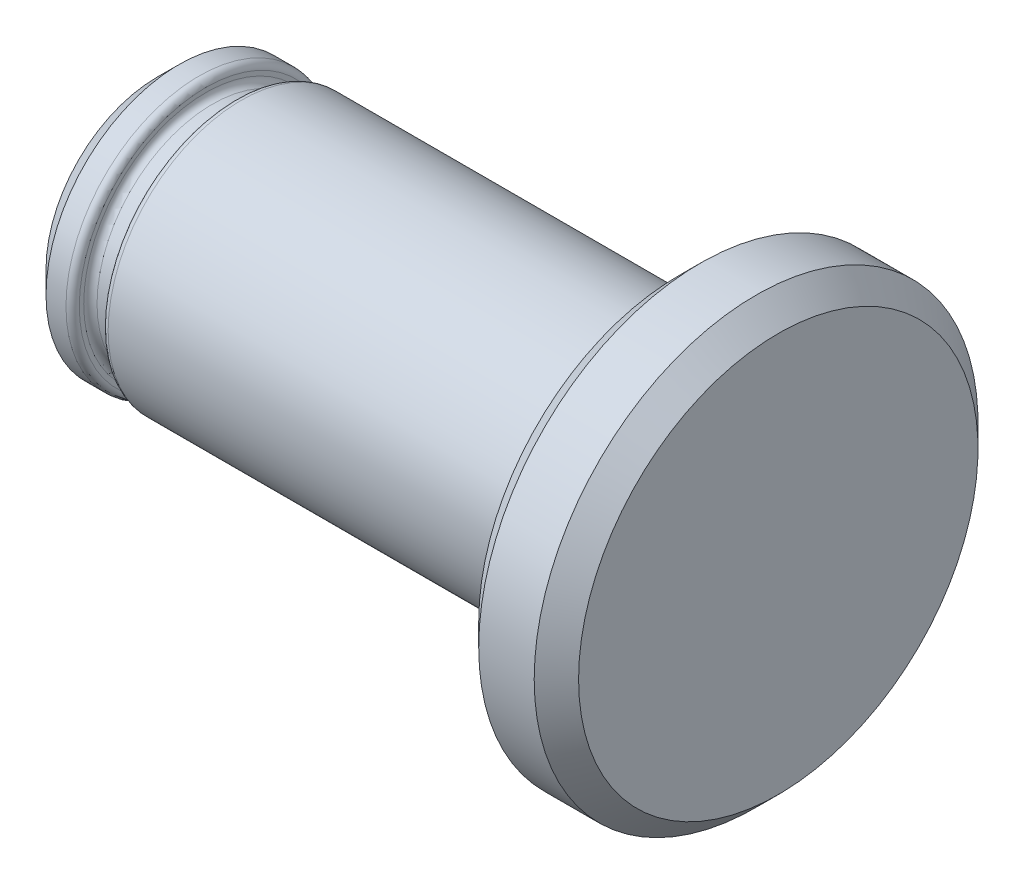
SolidWorks part; units mm, degrees
material "ABS"
ref_plane "Front Plane" through (0, 0, 0) normal (1, 0, 0) x (0, 1, 0)
ref_plane "Top Plane" through (0, 0, 0) normal (0, 0, 1) x (0, 1, 0)
ref_plane "Right Plane" through (0, 0, 0) normal (0, 1, 0) x (-1, 0, 0)
sketch "Sketch1" plane through (0, 0, 0) normal (0, 1, 0) x (-1, 0, 0)
  line L0 (0, 0) -> (0, 10) construction
  line L1 (-1, 10) -> (-3.5, 10)
  line L2 (-4.5, 9) -> (-4.5, 0)
  line L3 (-4.5, 0) -> (23.5, 0) construction
  line L4 (23.5, 0) -> (23.5, 5)
  line L5 (22.5, 6) -> (21.6, 6)
  line L6 (0, 9) -> (0, 8)
  line L7 (21.3, 5.7) -> (21.3, 5.5)
  line L8 (21, 5.2) -> (20.3, 5.2)
  line L9 (20, 5.5) -> (20, 5.7)
  line L10 (19.7, 6) -> (2, 6)
  line L11 (23.5, 5) -> (22.5, 6)
  line L12 (-1, 10) -> (0, 9)
  line L13 (-3.5, 10) -> (-4.5, 9)
  line L14 (23.5, 0) -> (-4.5, 0)
  arc A0 (2, 6) -> (0, 8) centre (2, 8) cw
  arc A1 (21.3, 5.7) -> (21.6, 6) centre (21.6, 5.7) cw
  arc A2 (21.3, 5.5) -> (21, 5.2) centre (21, 5.5) cw
  arc A3 (20.3, 5.2) -> (20, 5.5) centre (20.3, 5.5) cw
  arc A4 (20, 5.7) -> (19.7, 6) centre (19.7, 5.7) ccw
  point P4 (-4.5, 10)
  point P7 (23.5, 6)
  point P20 (0, 6)
  point P25 (21.3, 5.2)
  point P28 (20, 5.2)
  point P31 (20, 6)
  dimension "D8" = 2
  dimension "D9" = 0.3
  dimension "D1" = 12
  dimension "D2" = 20
  dimension "D3" = 4.5
  dimension "D4" = 3.5
  dimension "D5" = 0.8
  dimension "D6" = 20
  dimension "D7" = 1.3
revolve "Revolve1" add sketch "Sketch1" angle 360 about L14
